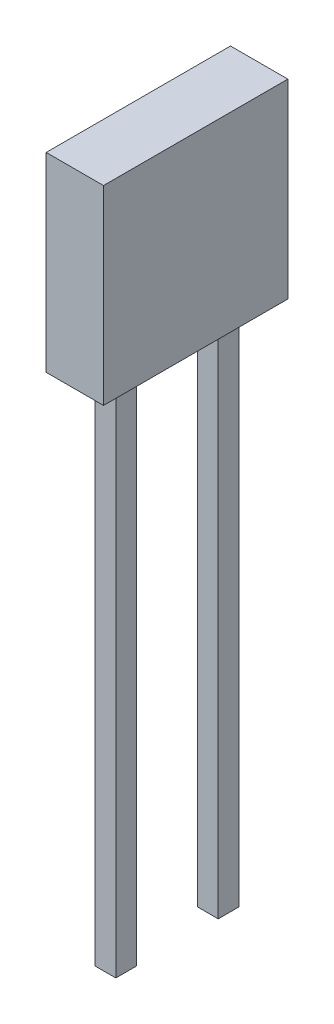
SolidWorks part; units mm, degrees
material "AISI 1020 Steel, Cold Rolled"
ref_plane "Alzado" through (0, 0, 0) normal (0, 0, 1) x (1, 0, 0)
ref_plane "Planta" through (0, 0, 0) normal (0, 1, 0) x (1, 0, 0)
ref_plane "Vista lateral" through (0, 0, 0) normal (1, 0, 0) x (0, 0, -1)
sketch "Croquis1" plane through (0, 0, 0) normal (0, 1, 0) x (1, 0, 0)
  line L1 (0, 4.5) -> (1.4, 4.5)
  line L2 (0, 4.5) -> (0, 0)
  line L3 (0, 0) -> (1.4, 0)
  line L4 (1.4, 4.5) -> (1.4, 0)
  dimension "D1" = 4.5
  dimension "D2" = 1.4
extrude "Saliente-Extruir1" add sketch "Croquis1" along normal blind 4.65
sketch "Croquis2" plane through (0, 0, 0) normal (0, -1, 0) x (1, 0, 0)
  line L2 (1.4, -2.25) -> (0, -2.25) construction
  line L3 (1.4, 0) -> (1.4, -4.5) construction
  line L4 (0, -4.5) -> (0, 0) construction
  line L5 (0.955, -0.745) -> (0.445, -0.745)
  line L6 (0.955, -0.745) -> (0.955, -1.255)
  line L7 (0.955, -1.255) -> (0.445, -1.255)
  line L8 (0.445, -0.745) -> (0.445, -1.255)
  line L9 (0.955, -0.745) -> (0.445, -1.255) construction
  line L10 (0.955, -1.255) -> (0.445, -0.745) construction
  line L11 (0.955, -3.755) -> (0.445, -3.755)
  line L12 (0.955, -3.755) -> (0.955, -3.245)
  line L13 (0.955, -3.245) -> (0.445, -3.245)
  line L14 (0.445, -3.755) -> (0.445, -3.245)
  line L15 (0.955, -3.755) -> (0.445, -3.245) construction
  line L16 (0.955, -3.245) -> (0.445, -3.755) construction
  line L17 (0.7, -4.5) -> (0.7, 0) construction
  line L18 (1.4, -4.5) -> (0, -4.5) construction
  line L19 (0, 0) -> (1.4, 0) construction
  dimension "D1" = 0.51
  dimension "D2" = 0.51
  dimension "D3" = 1.99
extrude "Saliente-Extruir2" add sketch "Croquis2" along normal blind 12.7
